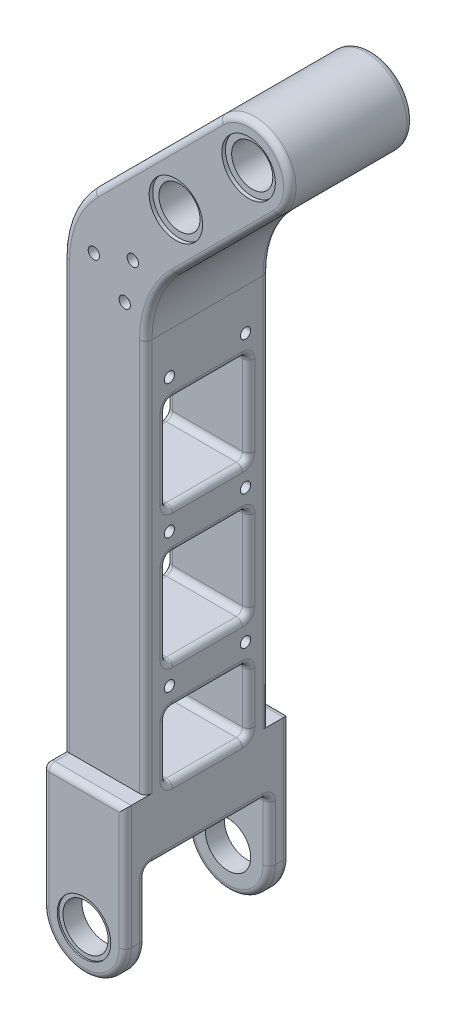
SolidWorks part; units mm, degrees
material "6061 合金"
ref_plane "前视基准面" through (0, 0, 0) normal (0, 0, 1) x (1, 0, 0)
ref_plane "上视基准面" through (0, 0, 0) normal (0, 1, 0) x (1, 0, 0)
ref_plane "右视基准面" through (0, 0, 0) normal (1, 0, 0) x (0, 0, -1)
other "Configuration Table"
sketch "草图1" plane through (0, 0, 0) normal (0, 0, 1) x (1, 0, 0)
  circle A0 centre (0, 0) radius 20
  circle A1 centre (0, 0) radius 10
  dimension "D1" = 40
  dimension "D2" = 20
extrude "凸台-拉伸1" add sketch "草图1" along normal blind 60 contours A1 | A0
ref_plane "基准面1" through (0, 0, 30) normal (0, 0, 1) x (1, 0, 0)
sketch "草图2" plane through (0, 0, 30) normal (0, 0, 1) x (1, 0, 0)
  line L0 (0, 0) -> (-70, -70) construction
  line L1 (-70, -70) -> (-70, -320) construction
  line L2 (0, -57.3148) -> (0, 49.9409) construction
  line L3 (-56.8582, 0) -> (46.4003, 0) construction
  line L4 (-14.1421, 14.1421) -> (-90, -61.7157)
  line L5 (14.1421, -14.1421) -> (-50, -78.2843)
  line L6 (-90, -61.7157) -> (-90, -320)
  line L7 (-50, -78.2843) -> (-50, -320)
  line L8 (-90, -320) -> (-50, -320)
  circle A2 centre (0, 0) radius 20 construction
  arc A3 (-14.1421, 14.1421) -> (14.1421, -14.1421) centre (0, 0) ccw
  dimension "D1" = 45
  dimension "D2" = 250
  dimension "D3" = 70
  dimension "D4" = 40
  dimension "D5" = 40
extrude "凸台-拉伸2" add sketch "草图2" along normal mid plane 60 contours L7 L8 L6 L4 A3 L5
sketch "草图4" plane through (0, 0, 60) normal (0, 0, 1) x (1, 0, 0)
  line L0 (-90, -61.7157) -> (-90, -320) construction
  line L1 (-90, -290) -> (-50, -290)
  line L2 (-90, -290) -> (-90, -350)
  line L4 (-50, -290) -> (-50, -350)
  line L5 (-50, -78.2843) -> (-50, -320) construction
  line L6 (-90, -320) -> (-50, -320) construction
  arc A0 (-90, -350) -> (-50, -350) centre (-70, -350) ccw
  circle A1 centre (-70, -350) radius 11
  dimension "D3" = 22
  dimension "D1" = 30
  dimension "D2" = 30
extrude "凸台-拉伸3" add sketch "草图4" along normal blind 10
mirror "镜向1" about plane through (0, 0, 30) normal (0, 0, 1) of "凸台-拉伸3"
sketch "草图5" plane through (0, 0, 0) normal (0, 1, 0) x (1, 0, 0)
  line L0 (0, 0) -> (0, -78.0582) construction
ref_plane "基准面2" through (-70, 0, 0) normal (-1, 0, 0) x (0, 0, 1)
sketch "草图7" plane through (-70, 0, 0) normal (-1, 0, 0) x (0, 0, 1)
  line L0 (-34.1239, -350) -> (109.535, -350) construction
sketch "草图8" plane through (0, 0, 60) normal (0, 0, 1) x (1, 0, 0)
  line L0 (0, 0) -> (-70, -70) construction
  circle A0 centre (-35.3553, -35.3553) radius 10
  dimension "D1" = 20
  dimension "D2" = 50
extrude "切除-拉伸1" cut sketch "草图8" against normal blind 100
fillet "圆角1" radius 50 2 edges at (-90, -61.7157, 30) (-50, -78.2843, 30)
fillet "圆角2" radius 3 34 edges at (-50, -320, 70) (-70, -370, 70) (-50, -335, 60) (-70, -370, 60) (-50, -335, 0) (-70, -370, 0) (-50, -320, -10) (-70, -370, -10) (-70, -320, 60) (-50, -320, 30) (-70, -320, 0) (-90, -290, 65) (-90, -320, 70) (-90, -335, 60) (-90, -320, 30) (-90, -335, 0) (-90, -320, -10) (-90, -290, -5) (-50, -194.4975, 0) (-46.194, -79.8608, 0) (-10.6066, -38.8909, 60) (-10.6066, -38.8909, 0) (14.1421, 14.1421, 0) (-44.7487, -16.4645, 0) (-44.7487, -16.4645, 60) (-86.194, -63.2922, 0) (-90, -186.2132, 0) (14.1421, 14.1421, 60) (-46.194, -79.8608, 60) (-50, -194.4975, 60) (-90, -186.2132, 60) (-86.194, -63.2922, 60) (-70, -290, 70) (-70, -290, -10)
sketch "草图9" plane through (0, 0, 70) normal (0, 0, 1) x (1, 0, 0)
  circle A0 centre (-70, -350) radius 13
  dimension "D1" = 26
extrude "切除-拉伸2" cut sketch "草图9" against normal blind 0.75
sketch "草图10" plane through (0, 0, -10) normal (0, 0, -1) x (-1, 0, 0)
  circle A0 centre (70, -350) radius 13
  dimension "D1" = 26
extrude "切除-拉伸3" cut sketch "草图10" against normal blind 0.75 contours A0
sketch "草图11" plane through (-90, 0, 0) normal (-1, 0, 0) x (0, 0, 1)
  circle A0 centre (48.5, -118.9949) radius 2.5
  circle A1 centre (48.5, -183.9949) radius 2.5
  circle A2 centre (48.5, -248.9949) radius 2.5
  circle A3 centre (11.5, -248.9949) radius 2.5
  circle A4 centre (11.5, -183.9949) radius 2.5
  circle A5 centre (11.5, -118.9949) radius 2.5
  point P18 (48.5, -118.9949)
  point P19 (48.5, -118.9949)
  point P20 (0, 0)
  point P21 (0, 0)
  point P22 (0, 0)
  point P23 (0, 0)
  point P24 (0, 0)
  point P25 (0, 0)
  point P26 (0, 0)
  dimension "D1" = 5
extrude "切除-拉伸4" cut sketch "草图11" against normal through all contours A1 | A2 | A0 | A3 | A4 | A5
sketch "草图12" plane through (-90, 0, 0) normal (-1, 0, 0) x (0, 0, 1)
  line L0 (30, -62.0134) -> (30, -339.6946) construction
  line L1 (10, -128.9949) -> (50, -128.9949)
  line L2 (10, -128.9949) -> (10, -173.9949)
  line L3 (10, -173.9949) -> (50, -173.9949)
  line L4 (50, -128.9949) -> (50, -173.9949)
  line L5 (10, -193.9949) -> (50, -193.9949)
  line L6 (10, -193.9949) -> (10, -238.9949)
  line L7 (10, -238.9949) -> (50, -238.9949)
  line L8 (50, -193.9949) -> (50, -238.9949)
  line L9 (10, -258.9949) -> (50, -258.9949)
  line L10 (10, -258.9949) -> (10, -290)
  line L11 (10, -290) -> (50, -290)
  line L12 (50, -258.9949) -> (50, -290)
  line L13 (19.5, -173.9949) -> (40.5, -173.9949)
  line L14 (19.5, -173.9949) -> (19.5, -193.9949)
  line L15 (19.5, -193.9949) -> (40.5, -193.9949)
  line L16 (40.5, -173.9949) -> (40.5, -193.9949)
  line L17 (19.5, -238.9949) -> (40.5, -238.9949)
  line L18 (19.5, -238.9949) -> (19.5, -258.9949)
  line L19 (19.5, -258.9949) -> (40.5, -258.9949)
  line L20 (40.5, -238.9949) -> (40.5, -258.9949)
  line L21 (60, -82.4264) -> (60, -290) construction
  line L22 (0, -290) -> (0, -82.4264) construction
  line L23 (57, -320) -> (3, -320) construction
  circle A0 centre (48.5, -118.9949) radius 2.5 construction
  circle A1 centre (48.5, -183.9949) radius 2.5 construction
  circle A2 centre (48.5, -248.9949) radius 2.5 construction
  dimension "D1" = 10
  dimension "D2" = 10
  dimension "D3" = 10
  dimension "D4" = 8
  dimension "D5" = 10
  dimension "D6" = 10
  dimension "D7" = 10
  dimension "D8" = 30
extrude "减重" cut sketch "草图12" against normal through all contours L0 L1 L2 L3 | L15 L0 L17 L7 L8 L5 | L0 L5 L6 L7 | L19 L0 L11 L12 L9 | L0 L9 L10 L11 | L1 L0 L13 L3 L4
fillet "圆角3" radius 3 36 edges at (-90, -258.9949, 30) (-50, -258.9949, 30) (-50, -290, 30) (-90, -290, 30) (-50, -238.9949, 30) (-50, -193.9949, 30) (-90, -193.9949, 30) (-90, -238.9949, 30) (-50, -173.9949, 30) (-90, -173.9949, 30) (-50, -128.9949, 30) (-90, -128.9949, 30) (-70, -290, 10) (-90, -274.4975, 10) (-70, -258.9949, 10) (-50, -274.4975, 10) (-50, -274.4975, 50) (-70, -258.9949, 50) (-90, -274.4975, 50) (-70, -290, 50) (-50, -216.4949, 50) (-70, -193.9949, 50) (-90, -216.4949, 50) (-70, -238.9949, 50) (-70, -238.9949, 10) (-90, -216.4949, 10) (-70, -193.9949, 10) (-50, -216.4949, 10) (-70, -173.9949, 10) (-90, -151.4949, 10) (-70, -128.9949, 10) (-50, -151.4949, 10) (-50, -151.4949, 50) (-70, -128.9949, 50) (-90, -151.4949, 50) (-70, -173.9949, 50)
sketch "草图13" plane through (0, 0, 60) normal (0, 0, 1) x (1, 0, 0)
  circle A0 centre (0, 0) radius 13
  circle A1 centre (-35.3553, -35.3553) radius 13
  dimension "D1" = 26
  dimension "D2" = 26
extrude "切除-拉伸6" cut sketch "草图13" against normal blind 1.75
sketch "草图14" plane through (0, 0, 0) normal (0, 0, -1) x (-1, 0, 0)
  circle A0 centre (0, 0) radius 13
  circle A1 centre (35.3553, -35.3553) radius 13
  dimension "D1" = 26
  dimension "D2" = 26
extrude "切除-拉伸7" cut sketch "草图14" against normal blind 1.75
sketch "草图15" plane through (0, 0, 0) normal (0, 0, -1) x (-1, 0, 0)
  line L0 (0, 0) -> (70, -350) construction
  line L1 (56.2719, -67.2005) -> (60.1942, -86.8121) construction
  line L2 (70, -350) -> (204.3541, -323.1292) construction
  circle A0 centre (56.2719, -67.2005) radius 2.75
  circle A1 centre (75.2172, -73.6095) radius 2.75
  circle A2 centre (60.1942, -86.8121) radius 2.75
  point P6 (60.1942, -86.8121)
  dimension "D1" = 5.5
  dimension "D2" = 20
  dimension "D3" = 20
  dimension "D4" = 20
  dimension "D5" = 42
  dimension "D6" = 270
extrude "切除-拉伸8" cut sketch "草图15" against normal through all contours A2 | A0 | A1
ref_plane "基准面3" through (0, 0, 0) normal (0.9806, -0.1961, 0) x (0, 0, -1)
